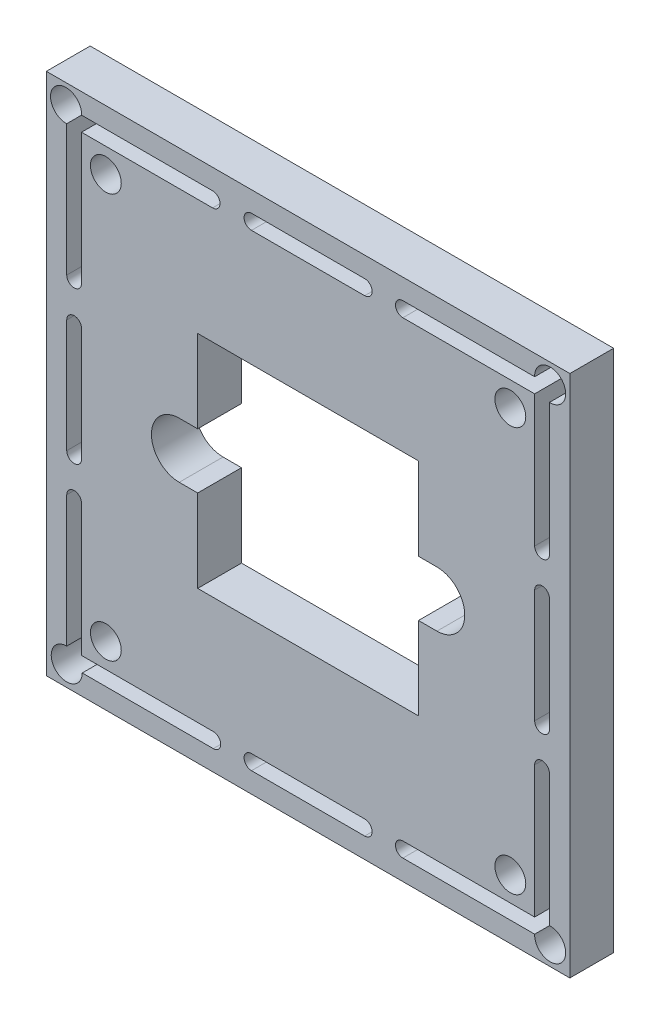
SolidWorks part; units mm, degrees
ref_plane "Front Plane" through (0, 0, 0) normal (0, 0, 1) x (1, 0, 0)
ref_plane "Top Plane" through (0, 0, 0) normal (0, 1, 0) x (1, 0, 0)
ref_plane "Right Plane" through (0, 0, 0) normal (1, 0, 0) x (0, 0, -1)
sketch "Sketch1" plane through (0, 0, 0) normal (0, 0, 1) x (1, 0, 0)
  line L1 (0, 37.9349) -> (37.9349, 37.9349)
  line L2 (0, 37.9349) -> (0, 0)
  line L3 (0, 0) -> (37.9349, 0)
  line L4 (37.9349, 37.9349) -> (37.9349, 0)
  dimension "D1" = 37.9349
extrude "Boss-Extrude1" add sketch "Sketch1" along normal blind 3.175
sketch "Sketch9" plane through (0, 0, 3.175) normal (0, 0, 1) x (1, 0, 0)
  line L0 (33.6232, 33.6232) -> (35.9219, 33.6232) construction
  line L1 (0, 0) -> (37.9349, 0) construction
  line L2 (2.5493, 18.9674) -> (1.4766, 18.9675) construction
  line L3 (33.6232, 35.922) -> (33.6232, 33.6232) construction
  line L4 (0, 37.9349) -> (0, 0) construction
  line L5 (35.3856, 12.1002) -> (36.4583, 12.1002) construction
  line L6 (4.3117, 35.9219) -> (4.3117, 33.6232) construction
  line L7 (2.013, 33.6232) -> (4.3117, 33.6232) construction
  line L8 (4.3117, 2.013) -> (4.3117, 4.3117) construction
  line L9 (2.0129, 4.3117) -> (4.3117, 4.3117) construction
  line L10 (35.9219, 4.3117) -> (33.6232, 4.3117) construction
  line L11 (33.6232, 2.013) -> (33.6232, 4.3117) construction
  line L12 (35.3856, 12.1002) -> (35.3856, 2.5493)
  line L13 (35.3856, 2.5493) -> (25.8347, 2.5493)
  line L14 (35.3856, 1.4766) -> (25.8347, 1.4766)
  line L15 (35.3856, 36.4583) -> (25.8347, 36.4583)
  line L16 (37.9349, 37.9349) -> (0, 37.9349) construction
  line L17 (12.0489, 36.4583) -> (2.5493, 36.4583)
  line L18 (12.0489, 36.4583) -> (12.0489, 35.3856) construction
  line L19 (12.0489, 35.3856) -> (2.5493, 35.3856)
  line L20 (35.922, 35.9219) -> (2.0129, 35.9219) construction
  line L21 (23.0695, 36.4583) -> (14.8653, 36.4583)
  line L22 (35.922, 35.9219) -> (35.922, 2.013) construction
  line L23 (35.922, 2.013) -> (2.013, 2.013) construction
  line L24 (2.0129, 35.9219) -> (2.013, 2.013) construction
  line L25 (18.9674, 37.9349) -> (18.9674, 0) construction
  line L26 (23.0695, 36.4583) -> (23.0695, 35.3856) construction
  line L27 (23.0695, 35.3856) -> (14.8653, 35.3856)
  line L28 (0, 0) -> (37.9349, 0) construction
  line L29 (25.8347, 2.5493) -> (25.8347, 1.4766) construction
  line L30 (14.8653, 36.4583) -> (14.8653, 35.3856) construction
  line L31 (35.3856, 2.5493) -> (36.4583, 2.5493) construction
  line L32 (35.922, 18.9674) -> (2.013, 18.9674) construction
  line L33 (2.5493, 36.4583) -> (2.5493, 35.3856) construction
  line L34 (2.5493, 35.3856) -> (1.4766, 35.3856) construction
  line L35 (2.5493, 12.1002) -> (1.4766, 12.1002) construction
  line L36 (36.4583, 12.1002) -> (36.4583, 2.5493)
  line L37 (35.3856, 35.3856) -> (25.8347, 35.3856)
  line L38 (2.5493, 35.3856) -> (2.5493, 25.886)
  line L39 (12.1002, 2.5493) -> (12.1002, 1.4766) construction
  line L42 (25.8347, 36.4583) -> (25.8347, 35.3856) construction
  line L43 (35.3856, 35.3856) -> (36.4583, 35.3856) construction
  line L44 (35.3856, 35.3856) -> (35.3856, 25.8347)
  line L45 (35.3856, 25.8347) -> (36.4583, 25.8347) construction
  line L46 (36.4583, 35.3856) -> (36.4583, 25.8347)
  line L47 (2.5493, 25.886) -> (1.4766, 25.886) construction
  line L48 (1.4766, 35.3856) -> (1.4766, 25.886)
  line L49 (2.5493, 23.0696) -> (1.4766, 23.0696) construction
  line L50 (2.5493, 23.0696) -> (2.5493, 14.8654)
  line L51 (2.5493, 14.8654) -> (1.4766, 14.8654) construction
  line L52 (1.4766, 23.0696) -> (1.4766, 14.8654)
  line L53 (36.4583, 18.9675) -> (35.3856, 18.9675) construction
  line L54 (36.4583, 23.0695) -> (35.3856, 23.0695) construction
  line L55 (36.4583, 23.0695) -> (36.4583, 14.8654)
  line L56 (36.4583, 14.8654) -> (35.3856, 14.8654) construction
  line L57 (35.3856, 23.0695) -> (35.3856, 14.8654)
  line L58 (18.9674, 36.4583) -> (18.9674, 35.3856) construction
  line L59 (18.9674, 2.5493) -> (18.9674, 1.4766) construction
  line L60 (23.0695, 2.5493) -> (14.8653, 2.5493)
  line L61 (23.0695, 2.5493) -> (23.0695, 1.4766) construction
  line L62 (23.0695, 1.4766) -> (14.8653, 1.4766)
  line L63 (14.8653, 2.5493) -> (14.8653, 1.4766) construction
  line L68 (2.5493, 12.1002) -> (2.5493, 2.5493)
  line L69 (1.4766, 12.1002) -> (1.4766, 2.6006)
  line L70 (2.5493, 2.5493) -> (12.1002, 2.5493)
  line L71 (2.6006, 1.4766) -> (12.1002, 1.4766)
  line L75 (12.1002, 2.013) -> (12.6365, 2.013) construction
  line L76 (2.013, 2.013) -> (2.013, 0) construction
  line L77 (0, 2.0129) -> (2.013, 2.013) construction
  circle A0 centre (33.6232, 33.6232) radius 1.1176
  circle A1 centre (4.3117, 33.6232) radius 1.1176
  circle A2 centre (4.3117, 4.3117) radius 1.1176
  circle A3 centre (33.6232, 4.3117) radius 1.1176
  arc A4 (25.8347, 1.4766) -> (25.8347, 2.5493) centre (25.8347, 2.013) cw
  arc A5 (36.4583, 2.5493) -> (35.3856, 1.4766) centre (36.5084, 1.4265) cw
  arc A6 (14.8653, 36.4583) -> (14.8653, 35.3856) centre (14.8653, 35.9219) ccw
  arc A7 (23.0695, 36.4583) -> (23.0695, 35.3856) centre (23.0695, 35.9219) cw
  arc A8 (1.4766, 2.6006) -> (2.6006, 1.4766) centre (1.4766, 1.4766) ccw
  arc A9 (36.4583, 12.1002) -> (35.3856, 12.1002) centre (35.9219, 12.1002) ccw
  arc A10 (12.0489, 35.3856) -> (12.0489, 36.4583) centre (12.0489, 35.9219) ccw
  arc A11 (1.4766, 35.3856) -> (2.5493, 36.4583) centre (1.4265, 36.5084) cw
  arc A12 (36.4583, 25.8347) -> (35.3856, 25.8347) centre (35.922, 25.8347) cw
  arc A13 (25.8347, 35.3856) -> (25.8347, 36.4583) centre (25.8347, 35.9219) cw
  arc A14 (36.4583, 35.3856) -> (35.3856, 36.4583) centre (36.5084, 36.5084) ccw
  arc A15 (2.5493, 25.886) -> (1.4766, 25.886) centre (2.013, 25.886) cw
  arc A16 (2.5493, 23.0696) -> (1.4766, 23.0696) centre (2.0129, 23.0695) ccw
  arc A17 (1.4766, 14.8654) -> (2.5493, 14.8654) centre (2.0129, 14.8654) ccw
  arc A18 (1.4766, 12.1002) -> (2.5493, 12.1002) centre (2.0129, 12.1002) cw
  arc A19 (12.1002, 2.5493) -> (12.1002, 1.4766) centre (12.1002, 2.013) cw
  arc A20 (36.4583, 23.0695) -> (35.3856, 23.0695) centre (35.922, 23.0695) ccw
  arc A21 (36.4583, 14.8654) -> (35.3856, 14.8654) centre (35.922, 14.8653) cw
  arc A22 (14.8653, 2.5493) -> (14.8653, 1.4766) centre (14.8654, 2.0129) ccw
  arc A23 (23.0695, 1.4766) -> (23.0695, 2.5493) centre (23.0695, 2.0129) ccw
  point P47 (18.9674, 18.9674)
  point P66 (2.0129, 18.9674)
  point P89 (35.922, 18.9674)
  dimension "D1" = 9.4996
  dimension "D3" = 2.013
  dimension "D4" = 2.2352
  dimension "D6" = 8.2042
  dimension "D5" = 1.1239
  dimension "D7" = 1.0727
  dimension "D2" = 2.2987
extrude "Cut-Extrude2" cut sketch "Sketch9" against normal up to surface (3.175 mm away) up to face at (18.9674, 18.9675, 0)
sketch "Sketch10" plane through (0, 0, 0) normal (0, 0, -1) x (-1, 0, 0)
  line L0 (0, 18.9674) -> (-10.9664, 18.9674) construction
  line L1 (-26.9685, 26.9684) -> (-10.9665, 26.9684)
  line L2 (-26.9685, 26.9684) -> (-26.9685, 10.9664)
  line L3 (-26.9685, 10.9664) -> (-10.9665, 10.9664)
  line L4 (-10.9665, 26.9684) -> (-10.9665, 10.9664)
  line L7 (-18.9674, 37.9349) -> (-18.9674, 26.9685) construction
  line L8 (-37.9349, 37.9349) -> (0, 37.9349) construction
  line L9 (0, 37.9349) -> (0, 0) construction
  dimension "D1" = 16.002
extrude "Cut-Extrude3" cut sketch "Sketch10" against normal up to surface (3.175 mm away) up to face at (18.9674, 2.0129, 3.175)
sketch "Sketch11" plane through (0, 0, 0) normal (0, 0, -1) x (-1, 0, 0)
  line L2 (-10.9665, 16.9545) -> (-9.6279, 16.9545)
  line L3 (-10.9665, 16.9545) -> (-10.9665, 20.9804)
  line L4 (-10.9665, 20.9804) -> (-9.6279, 20.9804)
  line L5 (-28.307, 20.9804) -> (-26.9685, 20.9804)
  line L6 (-28.307, 20.9804) -> (-28.307, 16.9545) construction
  line L7 (-9.6279, 16.9545) -> (-9.6279, 20.9804) construction
  line L10 (-9.6279, 18.9674) -> (-7.6149, 18.9674) construction
  line L11 (-28.307, 16.9545) -> (-26.9685, 16.9545)
  line L12 (-26.9685, 20.9804) -> (-26.9685, 16.9545)
  line L13 (-30.32, 18.9674) -> (-28.307, 18.9674) construction
  line L14 (-10.9665, 10.9664) -> (-10.9665, 26.9684) construction
  line L15 (-26.9685, 26.9684) -> (-26.9685, 10.9664) construction
  arc A0 (-9.6279, 20.9804) -> (-9.6279, 16.9545) centre (-9.6279, 18.9674) cw
  arc A1 (-28.307, 16.9545) -> (-28.307, 20.9804) centre (-28.307, 18.9674) cw
  point P10 (-10.9665, 18.9674)
  point P19 (-26.9685, 18.9674)
  dimension "D2" = 1.3386
  dimension "D1" = 4.0259
  dimension "D3" = 2.013
extrude "Cut-Extrude4" cut sketch "Sketch11" against normal up to surface (3.175 mm away) up to face at (18.9675, 18.9674, 3.175)
